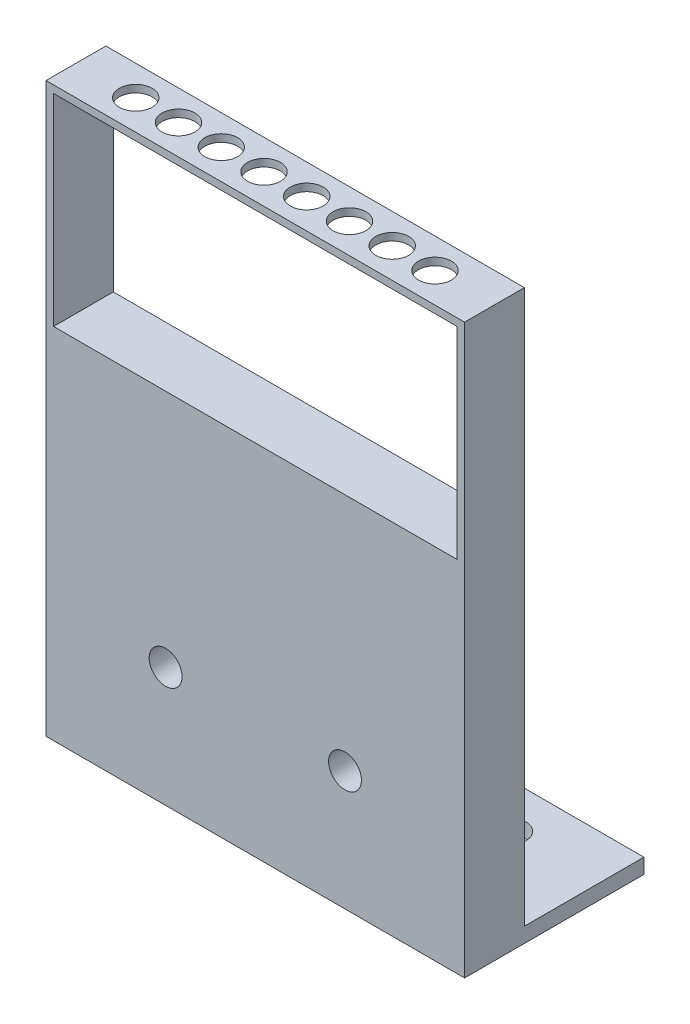
SolidWorks part; units mm, degrees
ref_plane "Front Plane" through (0, 0, 0) normal (0, 0, 1) x (1, 0, 0)
ref_plane "Top Plane" through (0, 0, 0) normal (0, 1, 0) x (1, 0, 0)
ref_plane "Right Plane" through (0, 0, 0) normal (1, 0, 0) x (0, 0, -1)
sketch "Sketch1" plane through (0, 0, 0) normal (0, 1, 0) x (1, 0, 0)
  line L1 (-44.45, -6.35) -> (44.45, -6.35)
  line L2 (-44.45, -6.35) -> (-44.45, 6.35)
  line L3 (-44.45, 6.35) -> (44.45, 6.35)
  line L4 (44.45, -6.35) -> (44.45, 6.35)
  line L5 (-44.45, -6.35) -> (44.45, 6.35) construction
  line L6 (-44.45, 6.35) -> (44.45, -6.35) construction
  point P0 (0, 0)
  dimension "D1" = 12.7
  dimension "D2" = 88.9
extrude "Boss-Extrude1" add sketch "Sketch1" along normal blind 76.2
sketch "Sketch2" plane through (0, 0, 0) normal (0, 1, 0) x (1, 0, 0)
  line L0 (-44.45, 6.35) -> (-44.45, -6.35) construction
  line L1 (-44.45, 22.225) -> (-44.45, 6.35)
  line L2 (-44.45, 6.35) -> (44.45, 6.35)
  line L3 (44.45, 31.75) -> (-44.45, 31.75)
  line L4 (-44.45, 22.225) -> (-44.45, 31.75)
  line L5 (0, 0) -> (-44.45, 31.75) construction
  line L6 (44.45, 31.75) -> (0, 0) construction
  line L7 (44.45, 6.35) -> (-44.45, 6.35) construction
  line L8 (-23.5905, 31.75) -> (-23.5905, 6.35) construction
  line L10 (44.45, 6.35) -> (44.45, 31.75)
  circle A0 centre (-25.4, 22.225) radius 3.4925
  circle A1 centre (0, 22.225) radius 3.4925
  circle A2 centre (25.4, 22.225) radius 3.4925
  point P0 (0, 0)
  point P15 (0, 0)
  point P19 (0, 0)
  point P20 (0, 0)
  point P21 (-44.45, 22.2984)
  dimension "D2" = 6.985
  dimension "D1" = 25.4
  dimension "D3" = 3
  dimension "D4" = 19.05
  dimension "D5" = 9.525
extrude "Boss-Extrude4" add sketch "Sketch2" along normal blind 3.175
sketch "Sketch3" plane through (0, 0, 6.35) normal (0, 0, 1) x (1, 0, 0)
  line L0 (-44.45, 76.2) -> (-44.45, 120.65)
  line L1 (-44.45, 120.65) -> (44.45, 120.65)
  line L2 (44.45, 120.65) -> (44.45, 76.2)
  line L3 (44.45, 76.2) -> (44.45, 0) construction
  line L4 (-44.45, 76.2) -> (-44.45, 0) construction
  line L5 (44.45, 76.2) -> (42.8625, 76.2)
  line L6 (-44.45, 76.2) -> (44.45, 76.2) construction
  line L7 (42.8625, 76.2) -> (42.8625, 119.0625)
  line L8 (42.8625, 119.0625) -> (-42.8625, 119.0625)
  line L9 (-42.8625, 119.0625) -> (-42.8625, 76.2)
  line L10 (-42.8625, 76.2) -> (-44.45, 76.2)
  line L11 (-42.8625, 119.0625) -> (-42.8625, 120.65) construction
  dimension "D1" = 1.5875
  dimension "D2" = 44.45
extrude "Boss-Extrude5" add sketch "Sketch3" against normal up to surface (12.7 mm away) up to face at (0, 39.6875, -6.35)
sketch "Sketch4" plane through (0, 120.65, 0) normal (0, 1, 0) x (1, 0, 0)
  line L0 (-44.45, 6.35) -> (-44.45, -6.35) construction
  circle A0 centre (-31.75, 0) radius 3.4925
  circle A1 centre (-22.6695, 0) radius 3.4925
  circle A2 centre (-13.589, 0) radius 3.4925
  circle A3 centre (-4.5085, 0) radius 3.4925
  circle A4 centre (4.572, 0) radius 3.4925
  circle A5 centre (13.6525, 0) radius 3.4925
  circle A6 centre (22.733, 0) radius 3.4925
  circle A7 centre (31.8135, 0) radius 3.4925
  dimension "D1" = 6.985
  dimension "D2" = 12.7
  dimension "D4" = 9.0805
  dimension "D3" = 8
extrude "Cut-Extrude1" cut sketch "Sketch4" against normal up to next
sketch "Sketch5" plane through (0, 0, 0) normal (0, 0, 1) x (1, 0, 0)
  line L0 (-44.45, 120.65) -> (-44.45, 0) construction
  line L1 (-44.45, 0) -> (44.45, 0) construction
  circle A0 centre (-19.05, 25.4) radius 3.4925
  circle A1 centre (19.05, 25.4) radius 3.4925
  dimension "D1" = 6.985
  dimension "D2" = 25.4
  dimension "D3" = 25.4
  dimension "D4" = 2
extrude "Cut-Extrude2" cut sketch "Sketch5" against normal through all both and the other way through all
